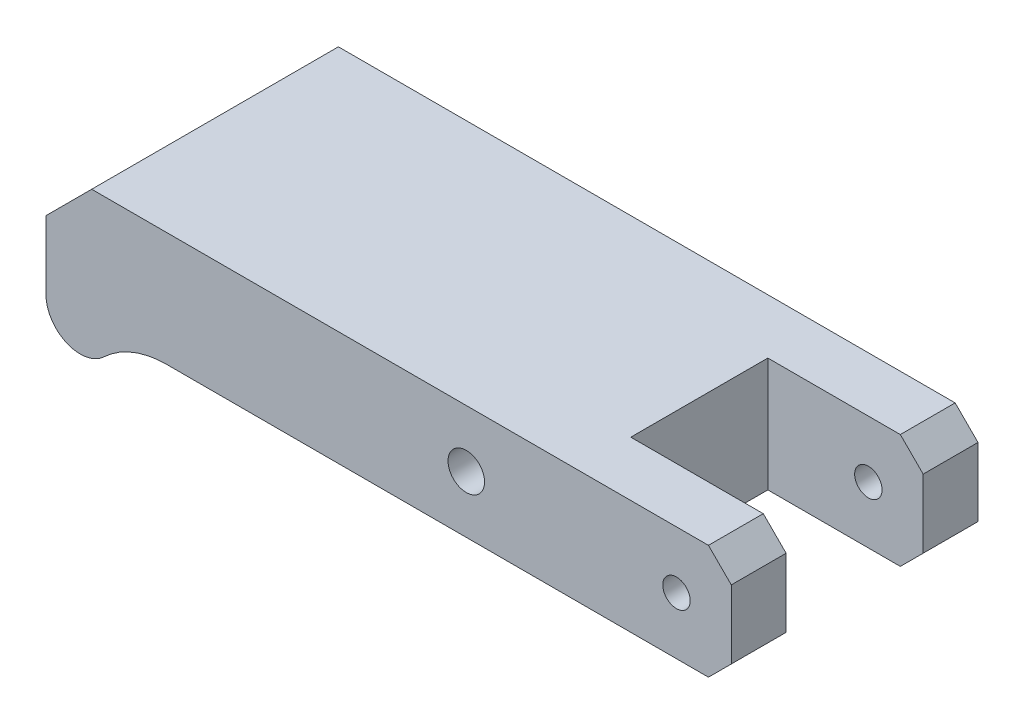
SolidWorks part; units mm, degrees
ref_plane "Piano frontale" through (0, 0, 0) normal (0, 0, 1) x (1, 0, 0)
ref_plane "Piano superiore" through (0, 0, 0) normal (0, 1, 0) x (1, 0, 0)
ref_plane "Piano destro" through (0, 0, 0) normal (1, 0, 0) x (0, 0, -1)
sketch "Schizzo1" plane through (0, 0, 0) normal (0, 0, 1) x (1, 0, 0)
  line L1 (-48.6254, -12.5) -> (75, -12.5)
  line L2 (-75, -12.5) -> (-75, 12.5)
  line L3 (-75, 12.5) -> (75, 12.5)
  line L4 (75, -12.5) -> (75, 12.5)
  line L5 (-75, -12.5) -> (75, 12.5) construction
  line L6 (-75, 12.5) -> (75, -12.5) construction
  circle A0 centre (63, 0) radius 3
  circle A1 centre (17, 0) radius 4
  arc A2 (-75, -12.5) -> (-62.3524, -17.9545) centre (-67.5, -12.5) ccw
  arc A3 (-62.3524, -17.9545) -> (-48.6254, -12.5) centre (-48.6254, -32.5) cw
  point P0 (0, 0)
  dimension "D4" = 6
  dimension "D6" = 8
  dimension "D7" = 15
  dimension "D8" = 20
  dimension "D1" = 150
  dimension "D2" = 25
  dimension "D3" = 12
  dimension "D5" = 58
  dimension "D9" = 9.462
extrude "Estrusione-Estrusione1" add sketch "Schizzo1" along normal blind 54
sketch "Schizzo2" plane through (75, 0, 0) normal (1, 0, 0) x (0, 0, -1)
  line L0 (-54, 12.5) -> (0, 12.5) construction
  line L1 (-42, 12.5) -> (-12, 12.5)
  line L2 (-42, 12.5) -> (-42, -12.5)
  line L3 (-42, -12.5) -> (-12, -12.5)
  line L4 (-12, 12.5) -> (-12, -12.5)
  line L5 (-54, -12.5) -> (0, -12.5) construction
  point P8 (-27, 12.5)
  dimension "D1" = 30
extrude "Taglio-Estrusione1" cut sketch "Schizzo2" against normal blind 34
chamfer "Smusso1" distance 5 angle 45 4 edges at (75, -12.5, 48) (75, -12.5, 6) (75, 12.5, 6) (75, 12.5, 48)
chamfer "Smusso2" distance 10 angle 45 1 edges at (-75, 12.5, 27)
